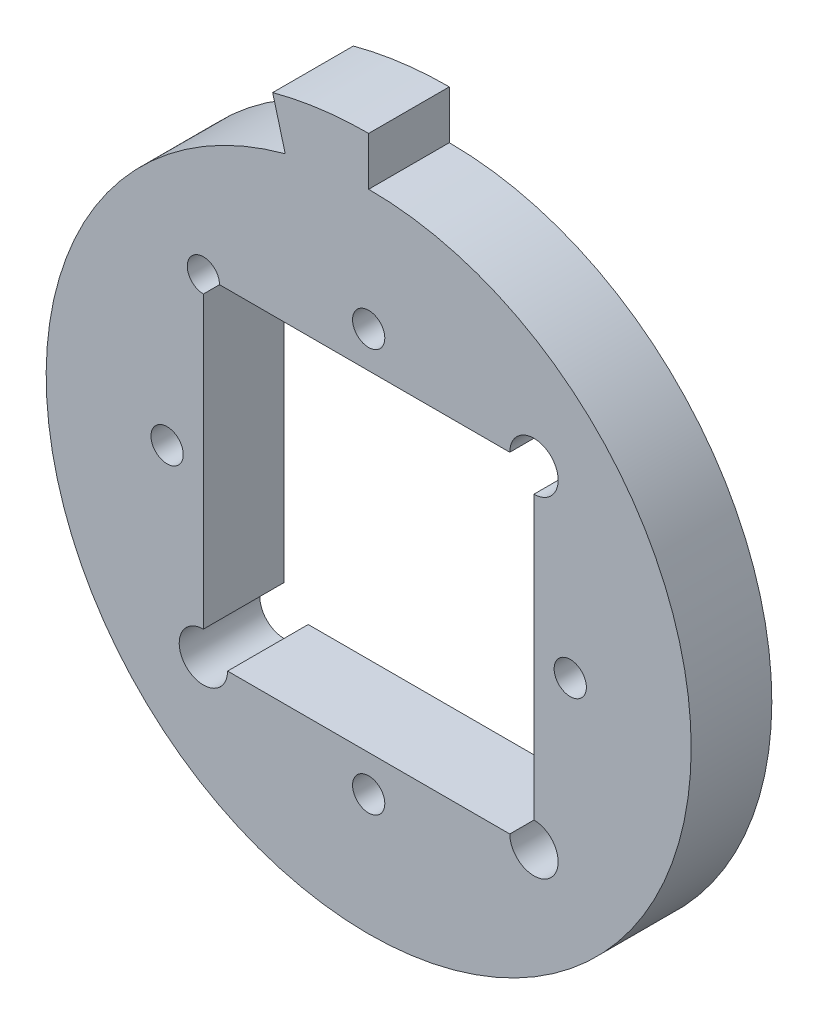
SolidWorks part; units mm, degrees
ref_plane "前视基准面" through (0, 0, 0) normal (0, 0, 1) x (1, 0, 0)
ref_plane "上视基准面" through (0, 0, 0) normal (0, 1, 0) x (1, 0, 0)
ref_plane "右视基准面" through (0, 0, 0) normal (1, 0, 0) x (0, 0, -1)
sketch "草图1" plane through (0, 0, 0) normal (0, 0, 1) x (1, 0, 0)
  line L0 (0, 0) -> (0, 23) construction
  line L1 (-10.25, 10.25) -> (10.25, 10.25)
  line L2 (-10.25, 10.25) -> (-10.25, -10.25)
  line L3 (-10.25, -10.25) -> (10.25, -10.25)
  line L4 (10.25, 10.25) -> (10.25, -10.25)
  line L5 (-10.25, 10.25) -> (10.25, -10.25) construction
  line L6 (-10.25, -10.25) -> (10.25, 10.25) construction
  line L7 (0, 0) -> (-5.9528, 22.2163) construction
  line L8 (-5.9528, 22.2163) -> (-5.1764, 19.3185)
  line L9 (0, 23) -> (0, 20)
  circle A0 centre (-10.25, 10.25) radius 1
  circle A1 centre (10.25, 10.25) radius 1.5
  circle A2 centre (10.25, -10.25) radius 1.5
  circle A3 centre (-10.25, -10.25) radius 1.5
  circle A4 centre (0, 0) radius 20
  arc A5 (0, 23) -> (-5.9528, 22.2163) centre (0, 0) ccw
  point P0 (0, 0)
  dimension "D2" = 2
  dimension "D3" = 3
  dimension "D4" = 3
  dimension "D5" = 3
  dimension "D6" = 40
  dimension "D8" = 15
  dimension "D1" = 20.5
  dimension "D7" = 23
extrude "凸台-拉伸1" add sketch "草图1" along normal blind 5 contours A4 A3 L2 A0 L1 A1 L4 A2 L3 | L9 A5 L8 A4
sketch "草图2" plane through (0, 0, 5) normal (0, 0, 1) x (1, 0, 0)
  line L0 (0, 13.5) -> (0, 0) construction
  circle A0 centre (0, 12.5) radius 1
  circle A1 centre (12.5, 0) radius 1
  circle A2 centre (0, -12.5) radius 1
  circle A3 centre (-12.5, 0) radius 1
  point P13 (0, 0)
  dimension "D2" = 2
  dimension "D1" = 13.5
  dimension "D3" = 4
extrude "切除-拉伸1" cut sketch "草图2" against normal blind 5
